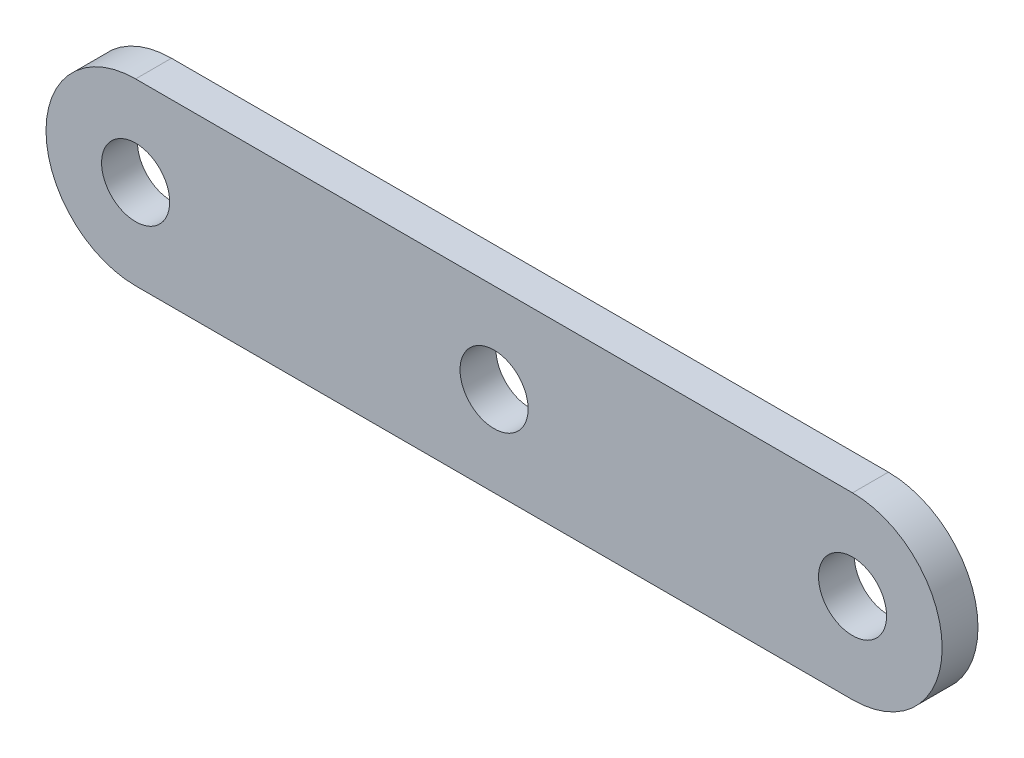
SolidWorks part; units mm, degrees
material "6061 Alloy"
ref_plane "Front Plane" through (0, 0, 0) normal (0, 0, 1) x (1, 0, 0)
ref_plane "Top Plane" through (0, 0, 0) normal (0, 1, 0) x (1, 0, 0)
ref_plane "Right Plane" through (0, 0, 0) normal (1, 0, 0) x (0, 0, -1)
sketch "Sketch1" plane through (0, 0, 0) normal (0, 0, 1) x (1, 0, 0)
  line L0 (-25.4, 6.35) -> (25.4, 6.35)
  line L1 (-25.4, -6.35) -> (25.4, -6.35)
  line L2 (-25.4, 6.35) -> (25.4, -6.35) construction
  arc A0 (25.4, 6.35) -> (25.4, -6.35) centre (25.4, 0) cw
  arc A1 (-25.4, 6.35) -> (-25.4, -6.35) centre (-25.4, 0) ccw
  dimension "D2" = 6.35
  dimension "D1" = 50.8
extrude "Boss-Extrude1" add sketch "Sketch1" along normal blind 2.54
sketch "Sketch2" plane through (0, 0, 2.54) normal (0, 0, 1) x (1, 0, 0)
  circle A0 centre (-25.4, 0) radius 2.413
  dimension "D1" = 4.826
extrude "Cut-Extrude1" cut sketch "Sketch2" against normal through all
pattern_linear "LPattern1" count 3 spacing 25.4 along (1, 0, 0) of "Cut-Extrude1"
